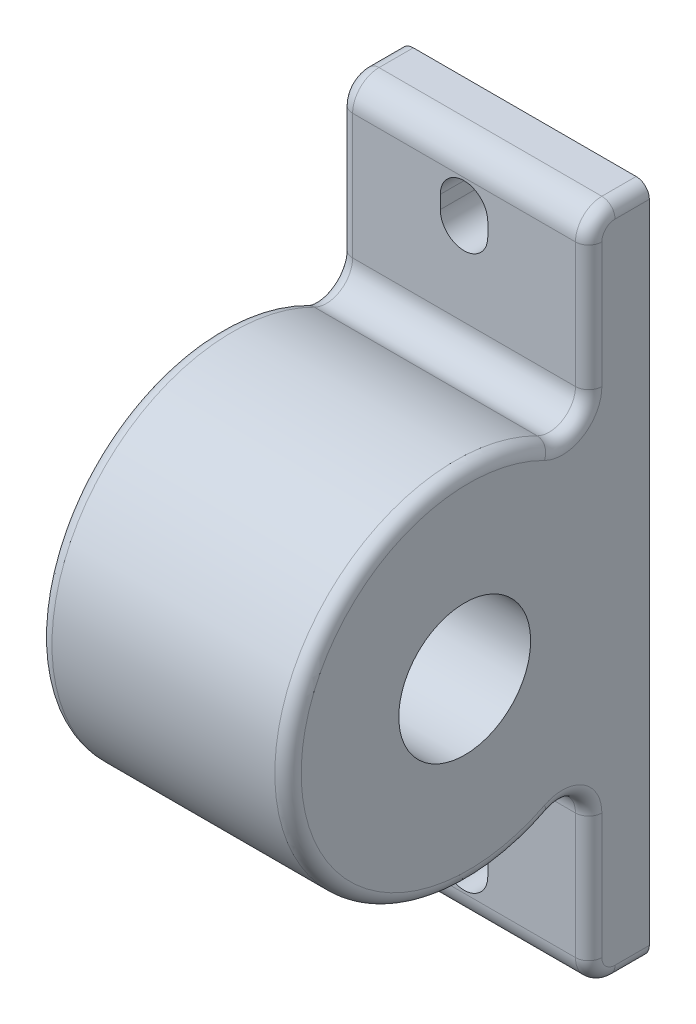
SolidWorks part; units mm, degrees
ref_plane "前视基准面" through (0, 0, 0) normal (0, 0, 1) x (1, 0, 0)
ref_plane "上视基准面" through (0, 0, 0) normal (0, 1, 0) x (1, 0, 0)
ref_plane "右视基准面" through (0, 0, 0) normal (1, 0, 0) x (0, 0, -1)
sketch "草图1" plane through (0, 0, 0) normal (0, 0, 1) x (1, 0, 0)
  line L1 (-47.25, -127.5) -> (47.25, -127.5)
  line L2 (-47.25, -127.5) -> (-47.25, 127.5)
  line L3 (-47.25, 127.5) -> (47.25, 127.5)
  line L4 (47.25, -127.5) -> (47.25, 127.5)
  line L5 (-47.25, -127.5) -> (47.25, 127.5) construction
  line L6 (-47.25, 127.5) -> (47.25, -127.5) construction
  point P0 (0, 0)
  dimension "D1" = 94.5
  dimension "D2" = 255
extrude "凸台-拉伸1" add sketch "草图1" along normal blind 137
sketch "草图2" plane through (47.25, 0, 0) normal (1, 0, 0) x (0, 0, -1)
  line L0 (0, 0) -> (-137, 0) construction
  line L1 (0, -127.5) -> (0, 127.5) construction
  line L2 (-137, -127.5) -> (-137, 127.5) construction
  line L3 (0, -127.5) -> (0, 127.5)
  line L4 (-23, -127.5) -> (-23, -51.2055)
  line L5 (-137, -127.5) -> (0, -127.5) construction
  line L6 (-23, -127.5) -> (0, -127.5)
  line L7 (-137, 127.5) -> (0, 127.5) construction
  line L8 (-23, 127.5) -> (0, 127.5)
  line L9 (-23, 51.2055) -> (-23, 127.5)
  line L11 (-23, -127.5) -> (-23, 127.5) construction
  arc A0 (-23, 51.2055) -> (-23, -51.2055) centre (-68.5, 0) ccw
  dimension "D1" = 23
extrude "切除-拉伸1" cut sketch "草图2" against normal blind 137 flip side to cut
fillet "圆角1" radius 10 4 edges at (0, 127.5, 23) (0, 51.2055, 23) (0, -51.2055, 23) (0, -127.5, 23)
fillet "圆角2" radius 5 18 edges at (-47.25, -127.5, 6.5) (-47.25, -124.5711, 20.0711) (-47.25, -93.7571, 23) (-47.25, -61.493, 27.7666) (-47.25, 127.5, 6.5) (-47.25, 124.5711, 20.0711) (-47.25, 93.7571, 23) (-47.25, 61.493, 27.7666) (-47.25, 0, 137) (47.25, 127.5, 6.5) (47.25, 124.5711, 20.0711) (47.25, 93.7571, 23) (47.25, 61.493, 27.7666) (47.25, 0, 137) (47.25, -61.493, 27.7666) (47.25, -93.7571, 23) (47.25, -124.5711, 20.0711) (47.25, -127.5, 6.5)
sketch "草图3" plane through (47.25, 0, 0) normal (1, 0, 0) x (0, 0, -1)
  line L0 (0, -122.5) -> (0, 122.5) construction
  line L1 (0, 0) -> (-122.2743, 0) construction
  circle A0 centre (-70, 0) radius 25
  dimension "D1" = 50
  dimension "D2" = 70
extrude "切除-拉伸2" cut sketch "草图3" against normal through all
sketch "草图4" plane through (0, 0, 0) normal (0, 0, -1) x (-1, 0, 0)
  line L0 (47.25, 0) -> (-47.25, 0) construction
  line L1 (47.25, 122.5) -> (47.25, -122.5) construction
  line L2 (-47.25, -122.5) -> (-47.25, 122.5) construction
  line L3 (0, 127.5) -> (0, -127.5) construction
  line L4 (-42.25, 127.5) -> (42.25, 127.5) construction
  line L5 (42.25, -127.5) -> (-42.25, -127.5) construction
  line L6 (9, 107.5) -> (9, 102.5)
  line L7 (-9, 107.5) -> (-9, 102.5)
  line L8 (9, 105) -> (-9, 105) construction
  line L9 (-9, -107.5) -> (-9, -102.5)
  line L10 (9, -107.5) -> (9, -102.5)
  arc A0 (9, 107.5) -> (-9, 107.5) centre (0, 107.5) ccw
  arc A1 (-9, 102.5) -> (9, 102.5) centre (0, 102.5) ccw
  arc A4 (-9, -102.5) -> (9, -102.5) centre (0, -102.5) cw
  arc A5 (9, -107.5) -> (-9, -107.5) centre (0, -107.5) cw
  dimension "D1" = 18
  dimension "D2" = 5
  dimension "D3" = 105
extrude "切除-拉伸3" cut sketch "草图4" against normal up to surface (23 mm away) up to face at (0, -93.7571, 23)
